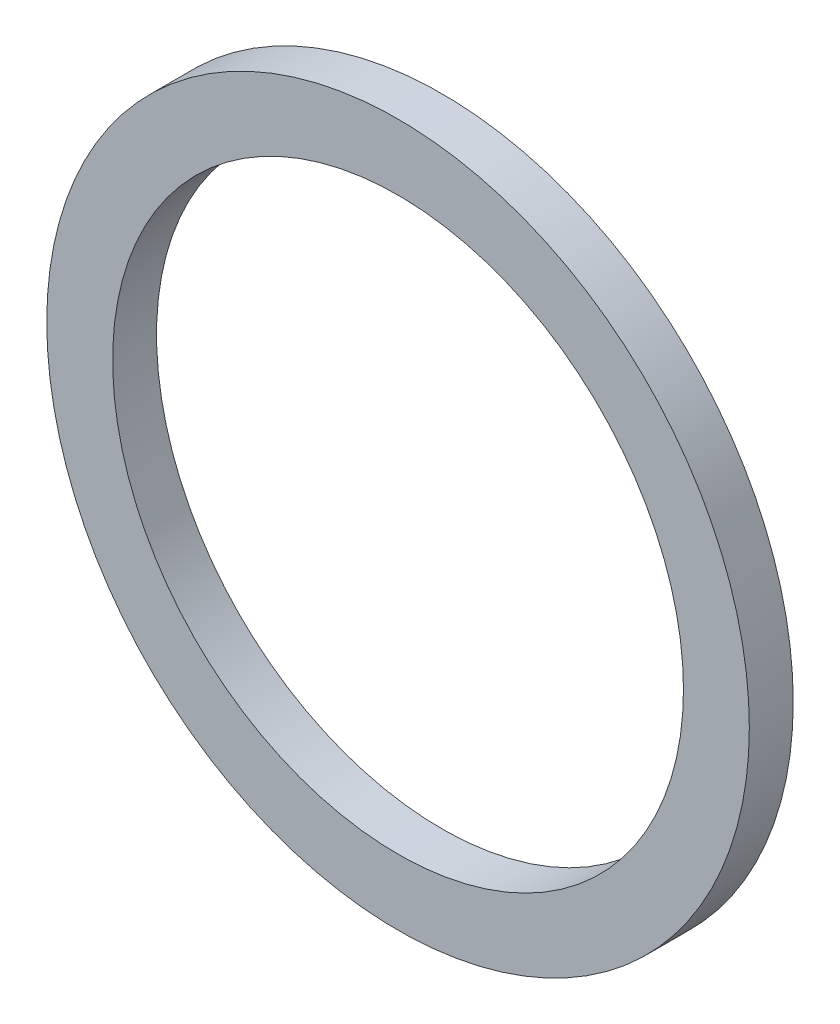
SolidWorks part; units mm, degrees
ref_plane "Front Plane" through (0, 0, 0) normal (0, 0, 1) x (1, 0, 0)
ref_plane "Top Plane" through (0, 0, 0) normal (0, 1, 0) x (1, 0, 0)
ref_plane "Right Plane" through (0, 0, 0) normal (1, 0, 0) x (0, 0, -1)
sketch "Sketch1" plane through (0, 0, 0) normal (0, 0, 1) x (1, 0, 0)
  circle A0 centre (0, 0) radius 95.25
  circle A1 centre (0, 0) radius 82.55
  circle A2 centre (0, 0) radius 101.6
  dimension "D1" = 190.5
  dimension "D2" = 12.7
  dimension "D3" = 6.35
extrude "Boss-Extrude1" add sketch "Sketch1" along normal blind 12.7 contours A0 A1 | A2 A0
